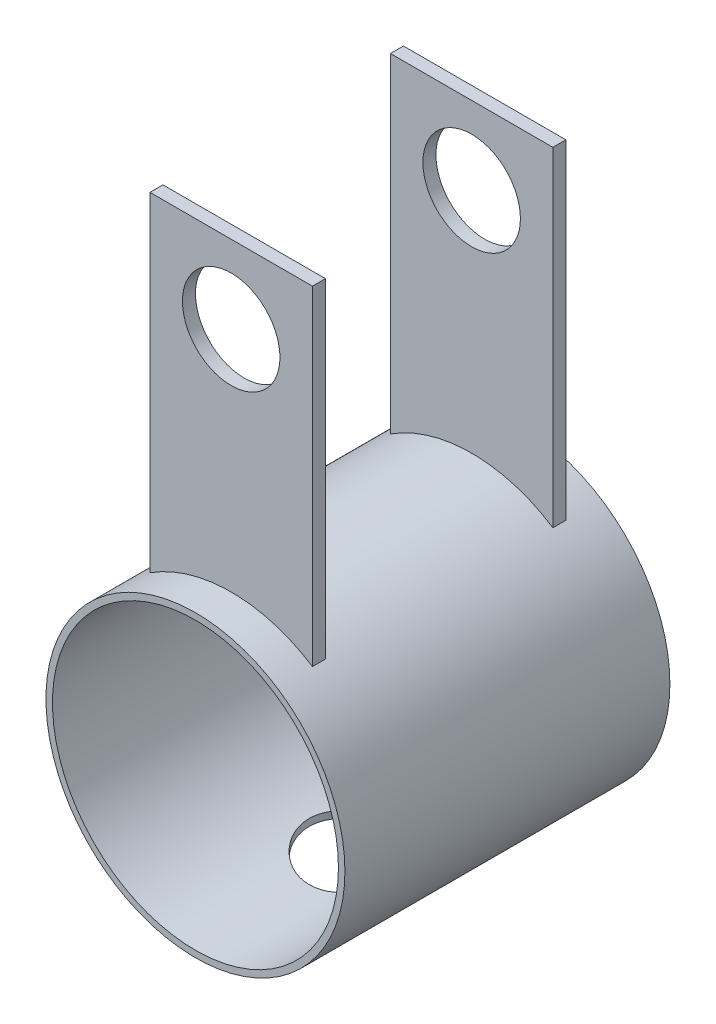
SolidWorks part; units mm, degrees
ref_plane "Plano frontal" through (0, 0, 0) normal (0, 0, 1) x (1, 0, 0)
ref_plane "Plano superior" through (0, 0, 0) normal (0, 1, 0) x (1, 0, 0)
ref_plane "Plano direito" through (0, 0, 0) normal (1, 0, 0) x (0, 0, -1)
sketch "Esboço1" plane through (0, 0, 0) normal (0, 0, 1) x (1, 0, 0)
  circle A0 centre (0, 0) radius 22
  circle A1 centre (0, 0) radius 23
  dimension "D1" = 44
  dimension "D2" = 46
extrude "Ressalto-extrusão1" add sketch "Esboço1" along normal blind 50
sketch "Esboço2" plane through (0, 0, 0) normal (0, 1, 0) x (1, 0, 0)
  circle A0 centre (0, -25) radius 7.5
  dimension "D1" = 15
extrude "Corte-extrusão1" cut sketch "Esboço2" against normal blind 50
sketch "Esboço3" plane through (0, 0, 0) normal (0, 1, 0) x (1, 0, 0)
  line L0 (23, -25) -> (0, -25)
  line L1 (23, -50) -> (23, 0) construction
  line L3 (0, -7.5) -> (-12.5, -7.5)
  line L4 (-12.5, -7.5) -> (-12.5, -5.5)
  line L5 (-12.5, -5.5) -> (12.5, -5.5)
  line L6 (12.5, -5.5) -> (12.5, -7.5)
  line L7 (12.5, -7.5) -> (0, -7.5)
  line L9 (0, -42.5) -> (-12.5, -42.5)
  line L10 (-12.5, -42.5) -> (-12.5, -44.5)
  line L11 (-12.5, -44.5) -> (12.5, -44.5)
  line L12 (12.5, -44.5) -> (12.5, -42.5)
  line L13 (12.5, -42.5) -> (0, -42.5)
  dimension "D1" = 17.5
  dimension "D2" = 12.5
  dimension "D3" = 2
  dimension "D4" = 25
  dimension "D5" = 2
  dimension "D6" = 17.5
  dimension "D7" = 12.5
  dimension "D8" = 2
  dimension "D9" = 25
extrude "Ressalto-extrusão2" add sketch "Esboço3" along normal blind 70 contours L9 L10 L11 L12 L13 | L5 L6 L7 L3 L4
sketch "Esboço4" plane through (0, 0, 5.5) normal (0, 0, -1) x (-1, 0, 0)
  circle A0 centre (0, 0) radius 22
extrude "Corte-extrusão2" cut sketch "Esboço4" against normal blind 70
sketch "Esboço7" plane through (0, 0, 5.5) normal (0, 0, -1) x (-1, 0, 0)
  line L0 (0, 23) -> (0, 58)
  arc A0 (12.5, 19.3067) -> (-12.5, 19.3067) centre (0, 0) ccw construction
  circle A1 centre (0, 58) radius 7.5
  dimension "D2" = 15
  dimension "D1" = 35
extrude "Corte-extrusão4" cut sketch "Esboço7" against normal blind 70
